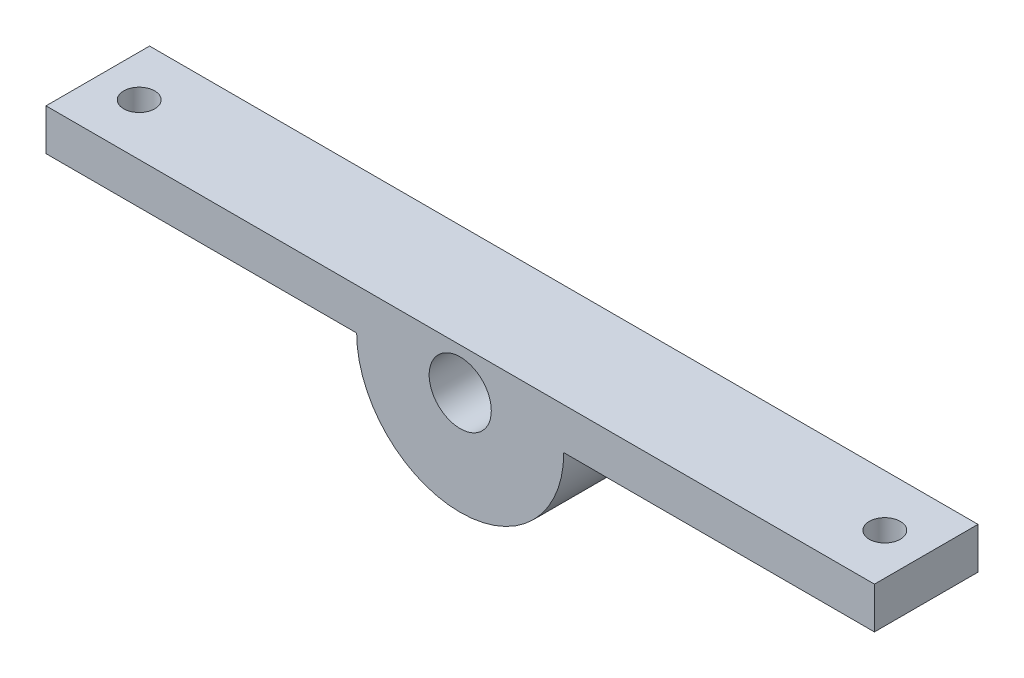
SolidWorks part; units mm, degrees
ref_plane "Plan de face" through (0, 0, 0) normal (0, 0, 1) x (1, 0, 0)
ref_plane "Plan de dessus" through (0, 0, 0) normal (0, 1, 0) x (1, 0, 0)
ref_plane "Plan de droite" through (0, 0, 0) normal (1, 0, 0) x (0, 0, -1)
sketch "Esquisse1" plane through (0, 0, 0) normal (0, 0, 1) x (1, 0, 0)
  line L21 (-10, 0) -> (-40, 0)
  line L23 (40, 4) -> (40, 0)
  line L24 (40, 0) -> (10, 0)
  line L25 (-40, 4) -> (-40, 0)
  line L27 (40, 4) -> (-40, 4)
  circle A0 centre (0, 0) radius 3
  arc A1 (-10, 0) -> (10, 0) centre (0, 0) ccw
  dimension "D1" = 6
  dimension "D2" = 20
  dimension "D3" = 80
  dimension "D4" = 40
  dimension "D5" = 4
extrude "Boss.-Extru.1" add sketch "Esquisse1" along normal blind 10
sketch "Esquisse2" plane through (0, 4, 0) normal (0, 1, 0) x (1, 0, 0)
  line L7 (-40, -10) -> (-40, 0) construction
  line L8 (40, -10) -> (40, 0) construction
  circle A0 centre (-36, -5) radius 1.5
  circle A1 centre (36, -5) radius 1.5
  dimension "D2" = 3
  dimension "D3" = 3
  dimension "D1" = 4
  dimension "D4" = 4
extrude "Enlèv. mat.-Extru.1" cut sketch "Esquisse2" against normal through all
